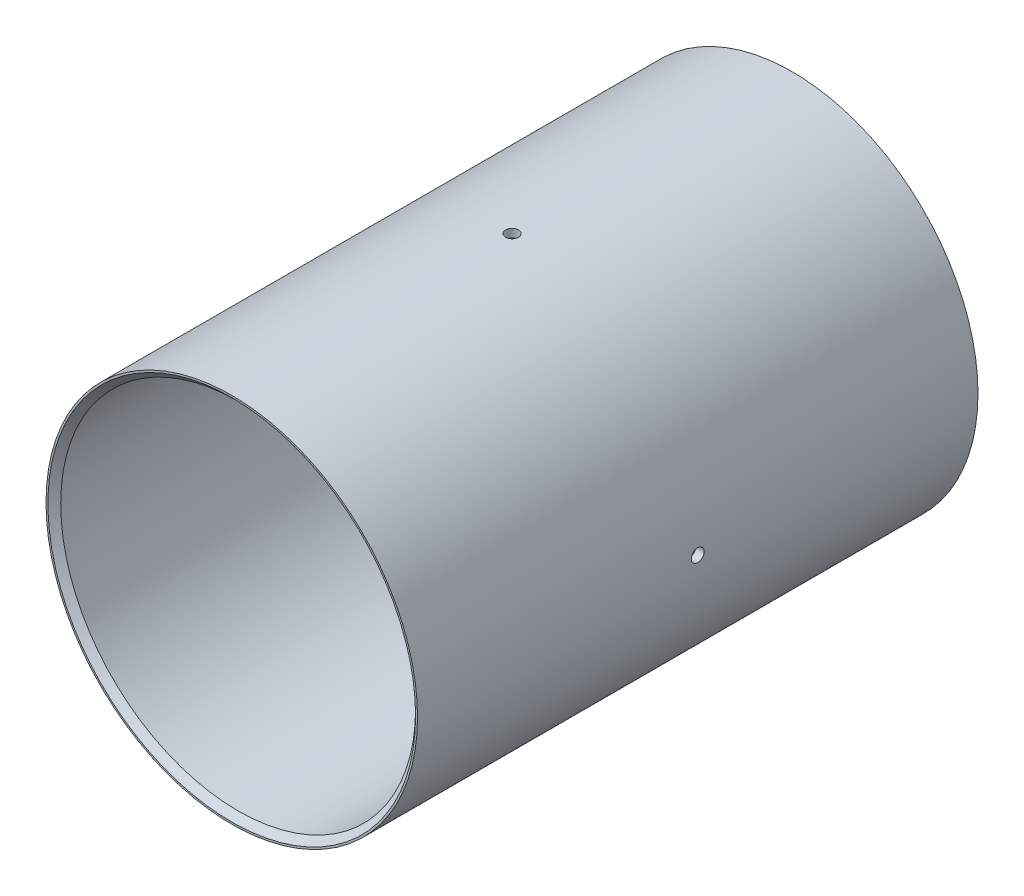
SolidWorks part; units mm, degrees
ref_plane "Front Plane" through (0, 0, 0) normal (0, 0, 1) x (1, 0, 0)
ref_plane "Top Plane" through (0, 0, 0) normal (0, 1, 0) x (1, 0, 0)
ref_plane "Right Plane" through (0, 0, 0) normal (1, 0, 0) x (0, 0, -1)
sketch "Sketch1" plane through (0, 0, 0) normal (0, 1, 0) x (1, 0, 0)
  line L0 (0, -37.3416) -> (0, 48.7638) construction
  line L1 (35.179, 73.7834) -> (35.179, -37.3416)
  line L2 (35.179, -37.3416) -> (36.83, -37.3416)
  line L3 (36.83, -37.3416) -> (36.83, 73.7834)
  line L4 (36.83, 73.7834) -> (35.179, 73.7834)
  dimension "D1" = 73.66
  dimension "D2" = 70.358
  dimension "D3" = 111.125
revolve "Revolve1" add sketch "Sketch1" angle 360 about L0
chamfer "Chamfer1" distance 1.27 angle 45 2 edges at (35.179, 0, -73.7834) (35.179, 0, 37.3416)
sketch "Sketch3" plane through (0, 0, 0) normal (0, 1, 0) x (1, 0, 0)
  line L0 (-36.83, -37.3416) -> (36.83, -37.3416) construction
  circle A0 centre (0, 18.2209) radius 1.27
  point P0 (0, 18.2209)
  dimension "D2" = 2.54
  dimension "D1" = 55.5625
extrude "ventholes" cut sketch "Sketch3" against normal through all both and the other way through all
pattern_circular "CirPattern1" count 2 over 90 about axis through (0, 0, 37.3416) along (0, 0, 1) of "ventholes"
